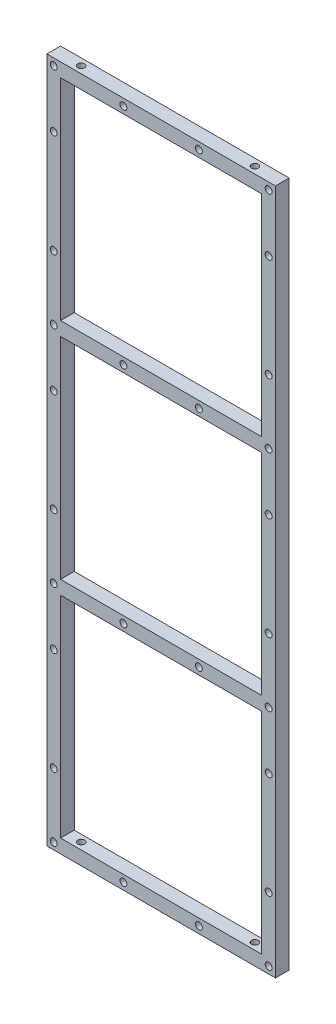
SolidWorks part; units mm, degrees
ref_plane "Front Plane" through (0, 0, 0) normal (0, 0, 1) x (1, 0, 0)
ref_plane "Top Plane" through (0, 0, 0) normal (0, 1, 0) x (1, 0, 0)
ref_plane "Right Plane" through (0, 0, 0) normal (1, 0, 0) x (0, 0, -1)
sketch "Sketch1" plane through (0, 0, 0) normal (0, 0, 1) x (1, 0, 0)
  line L0 (44, 144) -> (44, 52)
  line L9 (-50, -150) -> (50, -150)
  line L10 (-50, -150) -> (-50, 150)
  line L11 (-50, 150) -> (50, 150)
  line L12 (50, -150) -> (50, 150)
  line L15 (-44, -144) -> (44, -144)
  line L16 (-44, -144) -> (-44, -52)
  line L17 (-44, 144) -> (44, 144)
  line L21 (-44, 52) -> (44, 52)
  line L23 (-44, 46) -> (44, 46)
  line L25 (-44, -46) -> (44, -46)
  line L27 (-44, -52) -> (44, -52)
  line L33 (44, 46) -> (44, -46)
  line L34 (-44, 52) -> (-44, 144)
  line L35 (-44, -46) -> (-44, 46)
  line L36 (44, -52) -> (44, -144)
  point P0 (0, 0)
  point P6 (0, 0)
  point P20 (0, 0)
  dimension "D1" = 100
  dimension "D2" = 300
  dimension "D3" = 88
  dimension "D4" = 288
  dimension "D5" = 6
  dimension "D6" = 92
  dimension "D7" = 6
  dimension "D8" = 92
  dimension "D9" = 92
  dimension "D10" = 6
  dimension "D11" = 6
extrude "Boss-Extrude1" add sketch "Sketch1" along normal blind 6
sketch "Sketch2" plane through (0, 0, 6) normal (0, 0, 1) x (1, 0, 0)
  line L0 (-50, 150) -> (-44, 144)
  line L1 (44, 144) -> (50, 150)
  line L2 (44, -144) -> (50, -150)
  line L3 (-44, -144) -> (-50, -150)
  circle A0 centre (-47, 147) radius 1.5
  circle A1 centre (47, 147) radius 1.5
  circle A2 centre (47, 49) radius 1.5
  circle A3 centre (47, -49) radius 1.5
  circle A4 centre (47, -147) radius 1.5
  circle A5 centre (-47, 49) radius 1.5
  circle A6 centre (-47, -49) radius 1.5
  circle A7 centre (-47, -147) radius 1.5
  point P18 (47, 147)
  point P19 (-47, -147)
  dimension "D1" = 94
  dimension "D2" = 294
  dimension "D3" = 2
  dimension "D4" = 4
extrude "Cut-Extrude1" cut sketch "Sketch2" against normal blind 6 contours A0 | A1 | A5 | A2 | A6 | A3 | A7 | A4
sketch "Sketch3" plane through (0, 0, 6) normal (0, 0, 1) x (1, 0, 0)
  line L0 (50, 150) -> (-50, 150) construction
  line L1 (0, 150) -> (0, -150)
  line L2 (-50, -150) -> (50, -150) construction
  circle A0 centre (-47, 122) radius 1.5
  circle A1 centre (-47, 77) radius 1.5
  circle A2 centre (47, 122) radius 1.5
  circle A3 centre (47, 77) radius 1.5
  circle A4 centre (47, 24) radius 1.5
  circle A5 centre (47, -21) radius 1.5
  circle A6 centre (47, -74) radius 1.5
  circle A7 centre (47, -119) radius 1.5
  circle A8 centre (-47, 24) radius 1.5
  circle A9 centre (-47, -21) radius 1.5
  circle A10 centre (-47, -74) radius 1.5
  circle A11 centre (-47, -119) radius 1.5
  circle A12 centre (-16.5, 147) radius 1.5
  circle A13 centre (-16.5, 49) radius 1.5
  circle A14 centre (-16.5, -49) radius 1.5
  circle A15 centre (-16.5, -147) radius 1.5
  circle A16 centre (16.5, -147) radius 1.5
  circle A17 centre (16.5, -49) radius 1.5
  circle A18 centre (16.5, 49) radius 1.5
  circle A19 centre (16.5, 147) radius 1.5
  point P9 (0, 150)
  dimension "D1" = 28
  dimension "D6" = 16.5
  dimension "D2" = 45
  dimension "D3" = 28
  dimension "D4" = 2
  dimension "D5" = 3
  dimension "D7" = 4
extrude "Cut-Extrude2" cut sketch "Sketch3" against normal blind 10 contours A9 | A14 | A10 | A11 | A15 | A16 | A7 | A6 | A17 | A5 | A3 | A18 | A12 | A0 | A19 | A1 | A13 | A8 | A4 | A2
sketch "Sketch4" plane through (0, 150, 0) normal (0, 1, 0) x (1, 0, 0)
  line L0 (50, 0) -> (-50, 0) construction
  line L1 (-50, -6) -> (-50, 0) construction
  line L2 (0, -3.3) -> (0, 3.3) construction
  circle A0 centre (-38, -3) radius 1.5
  circle A1 centre (38, -3) radius 1.5
  dimension "D1" = 3
  dimension "D2" = 12
extrude "Cut-Extrude5" cut sketch "Sketch4" against normal blind 10
mirror "Mirror1" about plane through (0, 0, 0) normal (0, 1, 0) of "Cut-Extrude5"
